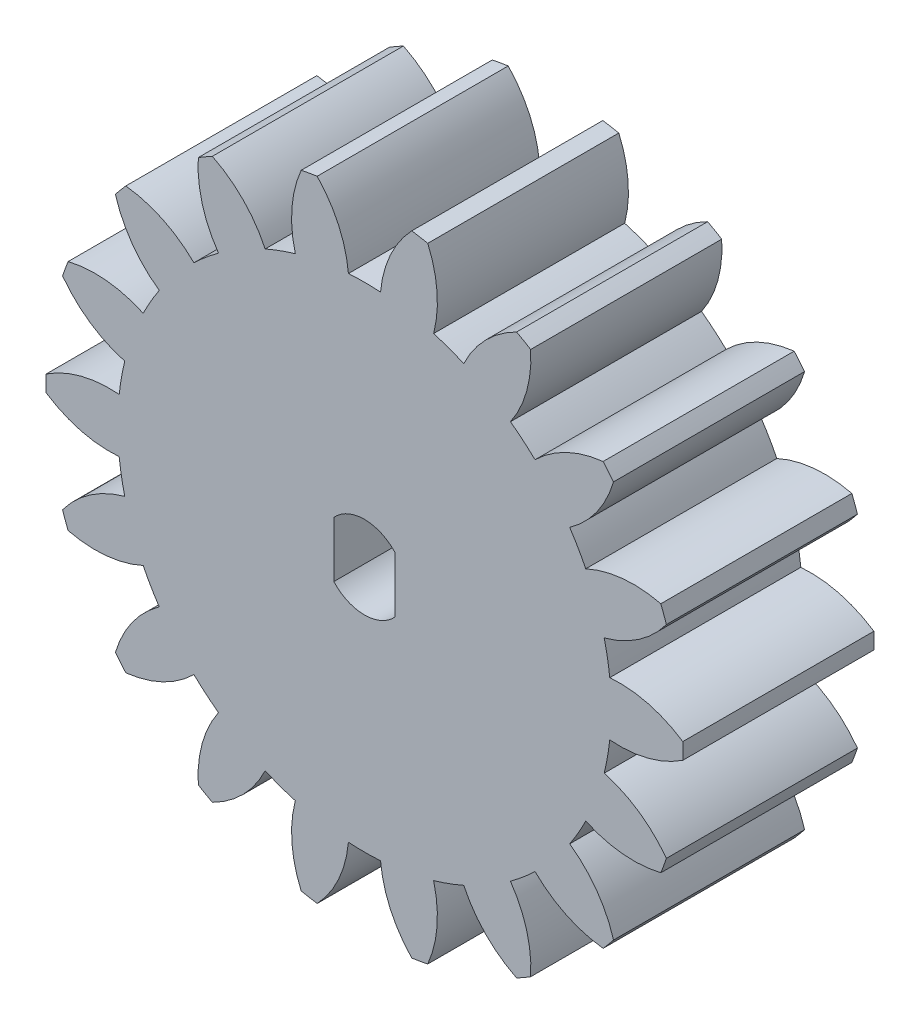
SolidWorks part; units mm, degrees
material "ABS"
ref_plane "Alzado" through (0, 0, 0) normal (0, 0, 1) x (1, 0, 0)
ref_plane "Planta" through (0, 0, 0) normal (0, 1, 0) x (1, 0, 0)
ref_plane "Vista lateral" through (0, 0, 0) normal (1, 0, 0) x (0, 0, -1)
sketch "Croquis2" plane through (0, 0, 0) normal (0, 0, 1) x (1, 0, 0)
  arc A0 (-15.6436, 12.4611) -> (-12.8902, 8.6059) centre (-8.7339, 14.4851) ccw
  arc A1 (-12.8902, 8.6059) -> (-13.898, 6.8603) centre (0, 0) ccw
  arc A2 (-13.898, 6.8603) -> (-18.6134, 7.3172) centre (-16.9114, 0.3212) ccw
  arc A3 (-18.6134, 7.3172) -> (-18.9621, 6.3592) centre (0, 0) ccw
  arc A4 (-18.9621, 6.3592) -> (-15.0562, 3.6782) centre (-13.1614, 10.6244) ccw
  arc A5 (-15.0562, 3.6782) -> (-15.4062, 1.6932) centre (0, 0) ccw
  arc A6 (-15.4062, 1.6932) -> (-19.9935, 0.5098) centre (-16.0014, -5.4822) ccw
  arc A7 (-19.9935, 0.5098) -> (-19.9935, -0.5098) centre (0, 0) ccw
  arc A8 (-19.9935, -0.5098) -> (-15.4062, -1.6932) centre (-16.0014, 5.4822) ccw
  arc A9 (-15.4062, -1.6932) -> (-15.0562, -3.6782) centre (0, 0) ccw
  arc A10 (-15.0562, -3.6782) -> (-18.9621, -6.3592) centre (-13.1614, -10.6244) ccw
  arc A11 (-18.9621, -6.3592) -> (-18.6134, -7.3172) centre (0, 0) ccw
  arc A12 (-18.6134, -7.3172) -> (-13.898, -6.8603) centre (-16.9114, -0.3212) ccw
  arc A13 (-13.898, -6.8603) -> (-12.8902, -8.6059) centre (0, 0) ccw
  arc A14 (-12.8902, -8.6059) -> (-15.6436, -12.4611) centre (-8.7339, -14.4851) ccw
  arc A15 (-15.6436, -12.4611) -> (-14.9882, -13.2421) centre (0, 0) ccw
  arc A16 (-14.9882, -13.2421) -> (-10.7135, -11.2) centre (-15.7817, -6.0859) ccw
  arc A17 (-10.7135, -11.2) -> (-9.1695, -12.4956) centre (0, 0) ccw
  arc A18 (-9.1695, -12.4956) -> (-10.4382, -17.06) centre (-3.253, -16.5987) ccw
  arc A19 (-10.4382, -17.06) -> (-9.5553, -17.5698) centre (0, 0) ccw
  arc A20 (-9.5553, -17.5698) -> (-6.2368, -14.1888) centre (-12.7484, -11.1165) ccw
  arc A21 (-6.2368, -14.1888) -> (-4.3427, -14.8782) centre (0, 0) ccw
  arc A22 (-4.3427, -14.8782) -> (-3.9738, -19.6012) centre (2.6203, -16.7103) ccw
  arc A23 (-3.9738, -19.6012) -> (-2.9698, -19.7783) centre (0, 0) ccw
  arc A24 (-2.9698, -19.7783) -> (-1.0078, -15.4662) centre (-8.1775, -14.8063) ccw
  arc A25 (-1.0078, -15.4662) -> (1.0078, -15.4662) centre (0, 0) ccw
  arc A26 (1.0078, -15.4662) -> (2.9698, -19.7783) centre (8.1775, -14.8063) ccw
  arc A27 (2.9698, -19.7783) -> (3.9738, -19.6012) centre (0, 0) ccw
  arc A28 (3.9738, -19.6012) -> (4.3427, -14.8782) centre (-2.6203, -16.7103) ccw
  arc A29 (4.3427, -14.8782) -> (6.2368, -14.1888) centre (0, 0) ccw
  arc A30 (6.2368, -14.1888) -> (9.5553, -17.5698) centre (12.7484, -11.1165) ccw
  arc A31 (9.5553, -17.5698) -> (10.4382, -17.06) centre (0, 0) ccw
  arc A32 (10.4382, -17.06) -> (9.1695, -12.4956) centre (3.253, -16.5987) ccw
  arc A33 (9.1695, -12.4956) -> (10.7135, -11.2) centre (0, 0) ccw
  arc A34 (10.7135, -11.2) -> (14.9882, -13.2421) centre (15.7817, -6.0859) ccw
  arc A35 (14.9882, -13.2421) -> (15.6436, -12.4611) centre (0, 0) ccw
  arc A36 (15.6436, -12.4611) -> (12.8902, -8.6059) centre (8.7339, -14.4851) ccw
  arc A37 (12.8902, -8.6059) -> (13.898, -6.8603) centre (0, 0) ccw
  arc A38 (13.898, -6.8603) -> (18.6134, -7.3172) centre (16.9114, -0.3212) ccw
  arc A39 (18.6134, -7.3172) -> (18.9621, -6.3592) centre (0, 0) ccw
  arc A40 (18.9621, -6.3592) -> (15.0562, -3.6782) centre (13.1614, -10.6244) ccw
  arc A41 (15.0562, -3.6782) -> (15.4062, -1.6932) centre (0, 0) ccw
  arc A42 (15.4062, -1.6932) -> (19.9935, -0.5098) centre (16.0014, 5.4822) ccw
  arc A43 (19.9935, -0.5098) -> (19.9935, 0.5098) centre (0, 0) ccw
  arc A44 (19.9935, 0.5098) -> (15.4062, 1.6932) centre (16.0014, -5.4822) ccw
  arc A45 (15.4062, 1.6932) -> (15.0562, 3.6782) centre (0, 0) ccw
  arc A46 (15.0562, 3.6782) -> (18.9621, 6.3592) centre (13.1614, 10.6244) ccw
  arc A47 (18.9621, 6.3592) -> (18.6134, 7.3172) centre (0, 0) ccw
  arc A48 (18.6134, 7.3172) -> (13.898, 6.8603) centre (16.9114, 0.3212) ccw
  arc A49 (13.898, 6.8603) -> (12.8902, 8.6059) centre (0, 0) ccw
  arc A50 (12.8902, 8.6059) -> (15.6436, 12.4611) centre (8.7339, 14.4851) ccw
  arc A51 (15.6436, 12.4611) -> (14.9882, 13.2421) centre (0, 0) ccw
  arc A52 (14.9882, 13.2421) -> (10.7135, 11.2) centre (15.7817, 6.0859) ccw
  arc A53 (10.7135, 11.2) -> (9.1695, 12.4956) centre (0, 0) ccw
  arc A54 (9.1695, 12.4956) -> (10.4382, 17.06) centre (3.253, 16.5987) ccw
  arc A55 (10.4382, 17.06) -> (9.5553, 17.5698) centre (0, 0) ccw
  arc A56 (9.5553, 17.5698) -> (6.2368, 14.1888) centre (12.7484, 11.1165) ccw
  arc A57 (6.2368, 14.1888) -> (4.3427, 14.8782) centre (0, 0) ccw
  arc A58 (4.3427, 14.8782) -> (3.9738, 19.6012) centre (-2.6203, 16.7103) ccw
  arc A59 (3.9738, 19.6012) -> (2.9698, 19.7783) centre (0, 0) ccw
  arc A60 (2.9698, 19.7783) -> (1.0078, 15.4662) centre (8.1775, 14.8063) ccw
  arc A61 (1.0078, 15.4662) -> (-1.0078, 15.4662) centre (0, 0) ccw
  arc A62 (-1.0078, 15.4662) -> (-2.9698, 19.7783) centre (-8.1775, 14.8063) ccw
  arc A63 (-2.9698, 19.7783) -> (-3.9738, 19.6012) centre (0, 0) ccw
  arc A64 (-3.9738, 19.6012) -> (-4.3427, 14.8782) centre (2.6203, 16.7103) ccw
  arc A65 (-4.3427, 14.8782) -> (-6.2368, 14.1888) centre (0, 0) ccw
  arc A66 (-6.2368, 14.1888) -> (-9.5553, 17.5698) centre (-12.7484, 11.1165) ccw
  arc A67 (-9.5553, 17.5698) -> (-10.4382, 17.06) centre (0, 0) ccw
  arc A68 (-10.4382, 17.06) -> (-9.1695, 12.4956) centre (-3.253, 16.5987) ccw
  arc A69 (-9.1695, 12.4956) -> (-10.7135, 11.2) centre (0, 0) ccw
  arc A70 (-10.7135, 11.2) -> (-14.9882, 13.2421) centre (-15.7817, 6.0859) ccw
  arc A71 (-14.9882, 13.2421) -> (-15.6436, 12.4611) centre (0, 0) ccw
  dimension "D1" = 15.499
  dimension "D2" = 20
extrude "Saliente-Extruir1" add sketch "Croquis2" along normal blind 12
sketch "Croquis3" plane through (0, 0, 12) normal (0, 0, 1) x (1, 0, 0)
  line L0 (-1.925, -1.7477) -> (-1.925, 1.7477)
  line L1 (0, 0) -> (0, 2.6) construction
  line L2 (1.925, -1.7477) -> (1.925, 1.7477)
  arc A0 (-1.925, -1.7477) -> (1.925, -1.7477) centre (0, 0) ccw
  arc A1 (1.925, 1.7477) -> (-1.925, 1.7477) centre (0, 0) ccw
  dimension "D1" = 5.2
  dimension "D2" = 3.85
extrude "Cortar-Extruir1" cut sketch "Croquis3" against normal through all both and the other way through all
sketch "Croquis4" plane through (0, 0, 12) normal (0, 0, 1) x (1, 0, 0)
  circle A0 centre (0, 0) radius 15.499
